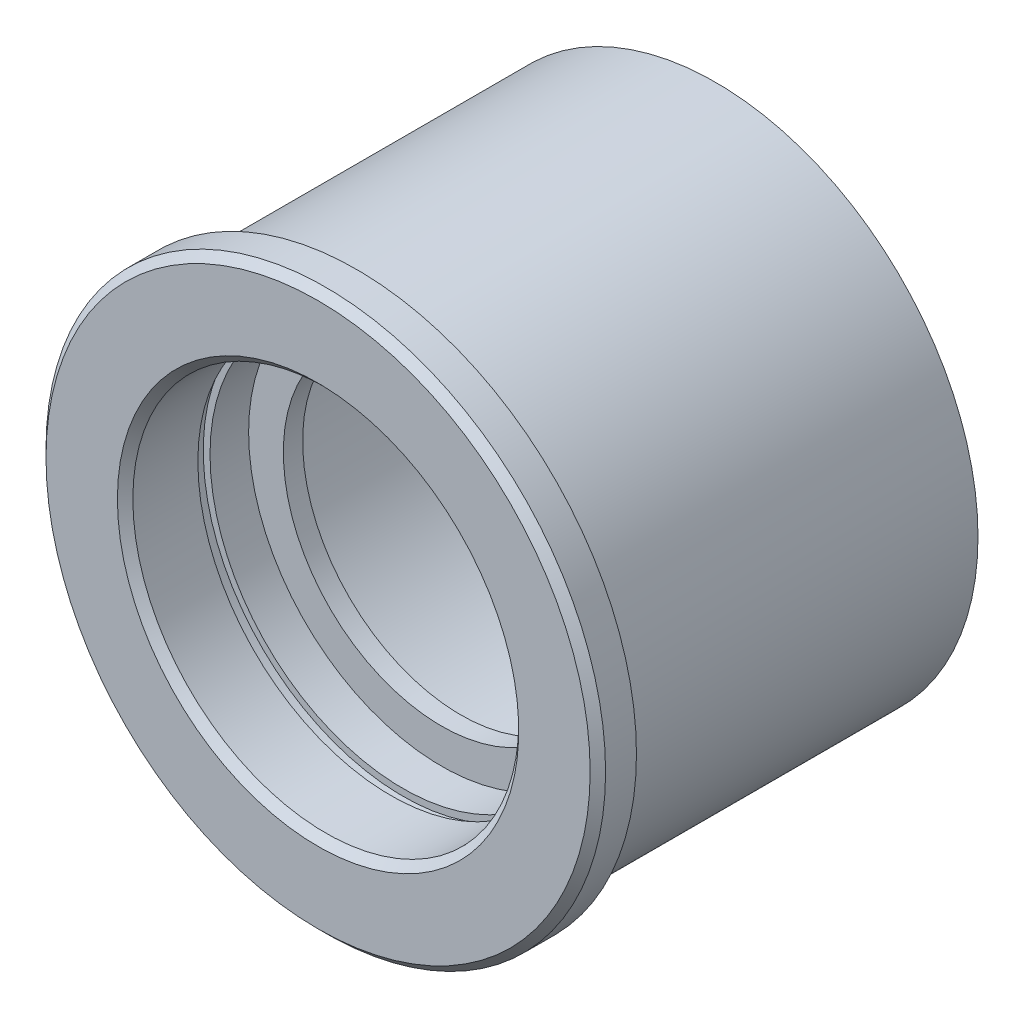
SolidWorks part; units mm, degrees
material "08Х18Н10 ГОСТ 4543-71"
ref_plane "Спереди" through (0, 0, 0) normal (0, 0, 1) x (1, 0, 0)
ref_plane "Сверху" through (0, 0, 0) normal (0, 1, 0) x (1, 0, 0)
ref_plane "Справа" through (0, 0, 0) normal (1, 0, 0) x (0, 0, -1)
sketch "Эскиз1" plane through (0, 0, 0) normal (1, 0, 0) x (0, 0, -1)
  line L0 (8.85, 50) -> (-10, 50)
  line L1 (0, 68) -> (93, 68)
  line L2 (93, 68) -> (93, 60)
  line L3 (93, 60) -> (83.15, 60)
  line L6 (22, 41) -> (22, 50)
  line L7 (22, 50) -> (12, 50)
  line L9 (0, 0) -> (110.0063, 0) construction
  line L10 (22, 41) -> (27, 41)
  line L11 (27, 41) -> (27, 50)
  line L12 (27, 50) -> (30, 50)
  line L13 (30, 50) -> (30, 60)
  line L15 (-10, 50) -> (-10, 72.5)
  line L16 (-10, 72.5) -> (0, 72.5)
  line L17 (0, -162) -> (0, 130) construction
  line L18 (0, 72.5) -> (0, 68)
  line L19 (8.85, 50) -> (8.85, 51.75)
  line L20 (8.85, 51.75) -> (12, 51.75)
  line L21 (12, 51.75) -> (12, 50)
  line L22 (79, 60) -> (79, 62)
  line L23 (79, 62) -> (83.15, 62)
  line L24 (83.15, 62) -> (83.15, 60)
  line L25 (79, 60) -> (30, 60)
  dimension "D2" = 100
  dimension "D3" = 82
  dimension "D4" = 120
  dimension "D5" = 22
  dimension "D6" = 5
  dimension "D7" = 8
  dimension "63" = 63
  dimension "D8" = 145
  dimension "D9" = 3
  dimension "D11" = 10
  dimension "D12" = 136
  dimension "D13" = 9.85
  dimension "D14" = 4.15
  dimension "D15" = 124
  dimension "D16" = 18.85
  dimension "D17" = 3.15
  dimension "D18" = 103.5
revolve "Повернуть1" add sketch "Эскиз1" angle 360 about L9
chamfer "Фаска2" distance 2 angle 45 3 edges at (60, 0, -93) (72.5, 0, 10) (50, 0, 10)
